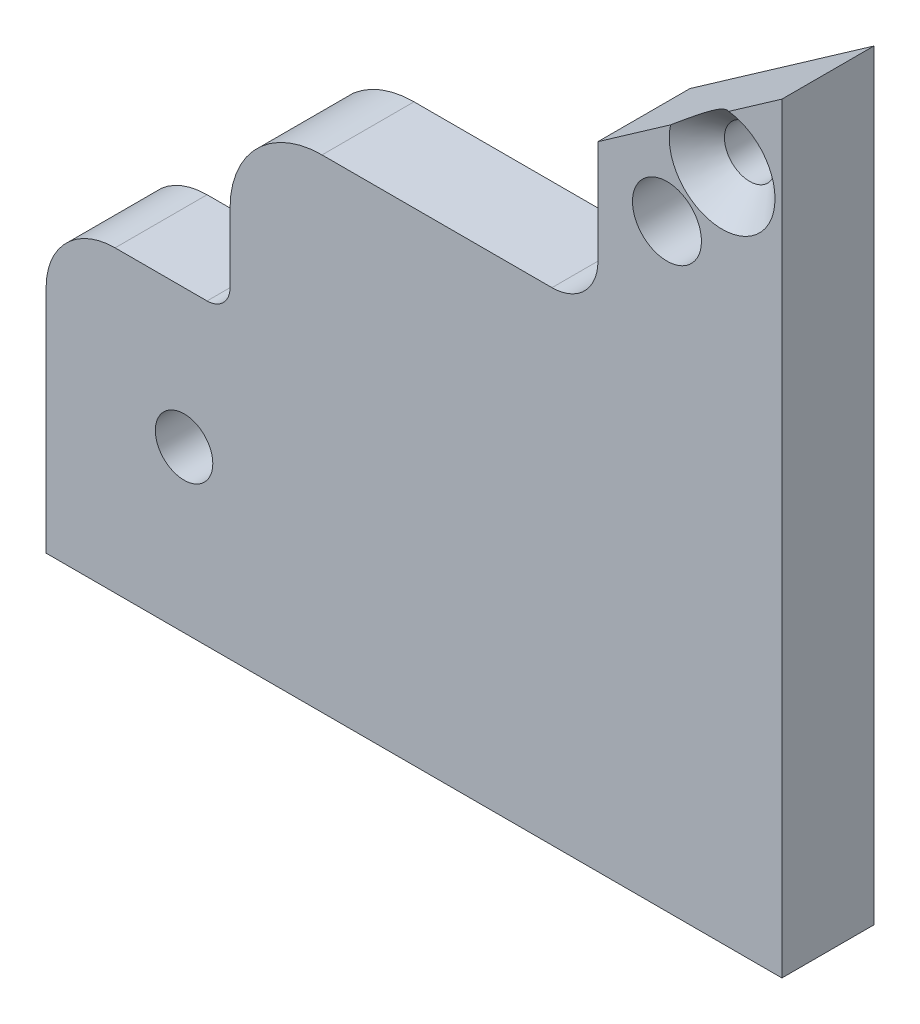
SolidWorks part; units mm, degrees
material "6061 Alloy"
ref_plane "Front Plane" through (0, 0, 0) normal (0, 0, 1) x (1, 0, 0)
ref_plane "Top Plane" through (0, 0, 0) normal (0, 1, 0) x (1, 0, 0)
ref_plane "Right Plane" through (0, 0, 0) normal (1, 0, 0) x (0, 0, -1)
ref_plane "Plane1" through (0, 0, 0) normal (0, 0, -1) x (-1, 0, 0)
sketch "Sketch1" plane through (0, 0, 0) normal (0, 0, -1) x (-1, 0, 0)
  line L0 (0, -2) -> (0, 31.1017)
  line L1 (0, 31.1017) -> (-32, 31.1017)
  line L2 (-32, 31.1017) -> (-32, -2)
  line L3 (-32, -2) -> (0, -2)
  dimension "D1" = 32
  dimension "D2" = 33.1017
extrude "Boss-Extrude1" add sketch "Sketch1" against normal blind 4
sketch "Sketch2" plane through (0, 0, 4) normal (0, 0, 1) x (1, 0, 0)
  line L0 (0, 11) -> (8, 11)
  line L1 (8, 11) -> (8, 31.1017)
  line L2 (8, 31.1017) -> (0, 31.1017)
  line L3 (0, 31.1017) -> (0, 11)
  dimension "D1" = 8
  dimension "D2" = 20.1017
extrude "Cut-Extrude1" cut sketch "Sketch2" against normal through all
sketch "Sketch3" plane through (0, 0, 4) normal (0, 0, 1) x (1, 0, 0)
  line L0 (8, 19) -> (24, 19)
  line L1 (24, 19) -> (24, 31.1017)
  line L2 (24, 31.1017) -> (8, 31.1017)
  line L3 (8, 31.1017) -> (8, 19)
  dimension "D1" = 16
  dimension "D2" = 12.1017
extrude "Cut-Extrude2" cut sketch "Sketch3" against normal through all
draft "Draft1" type of draft neutral plane draft angle 35 faces to draft 1 face at (28, 31.1017, 2) neutral plane through (32, 31.1017, 4) neutral plane normal (1, 0, 0) reverse direction yes parameters "D1"=35
ref_plane "Plane2" through (0, 5, 0) normal (0, -1, 0) x (1, 0, 0)
ref_plane "Plane3" through (0, 14, 0) normal (0, 1, 0) x (1, 0, 0)
hole_wizard "Ø3.0 (3) Diameter Hole1" positions "Sketch7" profile "Sketch6" hole size "Ø3.0" standard "ANSI Metric" end condition through all
sketch "Sketch7" plane through (0, 0, 4) normal (0, 0, 1) x (1, 0, 0)
  line L1 (24, 19) -> (24, 25.5) construction
  point P0 (27, 24)
  dimension "D1" = 3
  dimension "D2" = 1.5
sketch "Sketch6" plane through (27, 24, 4) normal (1, 0, 0) x (0, -1, 0)
  line L0 (0, 0) -> (0, 4)
  line L1 (0, 4) -> (1.5, 4)
  line L2 (1.5, 4) -> (1.5, 0)
  line L5 (1.5, 0) -> (0, 0)
  line L11 (0, -6.35) -> (0, 107.95) construction
  dimension "Thru Hole Dia." = 3
  dimension "Thru Hole Depth" = 4
hole_wizard "CSK for M3 SFHCS1" positions "Sketch11" profile "Sketch10" countersink size "M3" standard "ANSI Metric"
sketch "Sketch11" plane through (0, 0, 4) normal (0, 0, 1) x (1, 0, 0)
  line L8 (32, 31.1017) -> (32, -2) construction
  point P0 (29.4, 27.2)
  dimension "D1" = 2.6
  dimension "D2" = 1.7
sketch "Sketch10" plane through (29.4, 27.2, 4) normal (1, 0, 0) x (0, -1, 0)
  line L0 (0, 0) -> (0, 10.1609)
  line L1 (0, 10.1609) -> (1.1, 9.5)
  line L2 (1.1, 9.5) -> (1.1, 1.2)
  line L3 (1.1, 1.2) -> (2.3, 0)
  line L5 (2.3, 0) -> (0, 0)
  line L6 (-1.1, 1.2) -> (-2.3, 0) construction
  line L10 (0, 10.1609) -> (-1.1, 9.5) construction
  line L11 (0, -6.35) -> (0, 107.95) construction
  dimension "Hole Dia." = 2.2
  dimension "Hole Depth" = 9.5
  dimension "Near C'Sink Dia." = 4.6
  dimension "Near C'Sink Angle" = 90
  dimension "Drill Angle" = 118
hole_wizard "M3x0.5 Tapped Hole2" positions "Sketch13" profile "Sketch12" tap size "M3x0.5" standard "ANSI Metric"
sketch "Sketch13" plane through (0, -2, 0) normal (0, -1, 0) x (-1, 0, 0)
  point P0 (-10, -2)
  point P1 (-19.5, -2)
  point P2 (-29, -2)
sketch "Sketch12" plane through (10, -2, 2) normal (1, 0, 0) x (0, 0, -1)
  line L0 (0, 0) -> (0, 8.2511)
  line L1 (0, 8.2511) -> (1.25, 7.5)
  line L2 (1.25, 7.5) -> (1.25, 0)
  line L5 (1.25, 0) -> (0, 0)
  line L10 (0, 8.2511) -> (-1.25, 7.5) construction
  line L11 (0, -6.35) -> (0, 107.95) construction
  dimension "Tap Drill Dia." = 2.5
  dimension "Tap Drill Depth" = 7.5
  dimension "Drill Angle" = 118
fillet "Fillet1" radius 1 1 edges at (8, 11, 2)
fillet "Fillet2" radius 2 1 edges at (24, 19, 2)
fillet "Fillet3" radius 3 1 edges at (0, 11, 2)
fillet "Fillet4" radius 4 1 edges at (8, 19, 2)
hole_wizard "M3x0.5 Tapped Hole1" positions "3DSketch1" profile "Sketch14" tap size "M3x0.5" standard "ANSI Metric" end condition through all
sketch3d "3DSketch1"
  line L0 (0, -2, 4) -> (0, 8, 4) construction
  line L1 (32, -2, 4) -> (0, -2, 4) construction
  point P0 (6, 5, 4)
  dimension "D1" = 6
  dimension "D2" = 7
sketch "Sketch14" plane through (6, 5, 4) normal (1, 0, 0) x (0, -1, 0)
  line L0 (0, 0) -> (0, 4)
  line L1 (0, 4) -> (1.25, 4)
  line L2 (1.25, 4) -> (1.25, 0)
  line L5 (1.25, 0) -> (0, 0)
  line L11 (0, -6.35) -> (0, 107.95) construction
  dimension "Thread Major Dia." = 2.5
  dimension "Thru Tap Drill Depth" = 4
